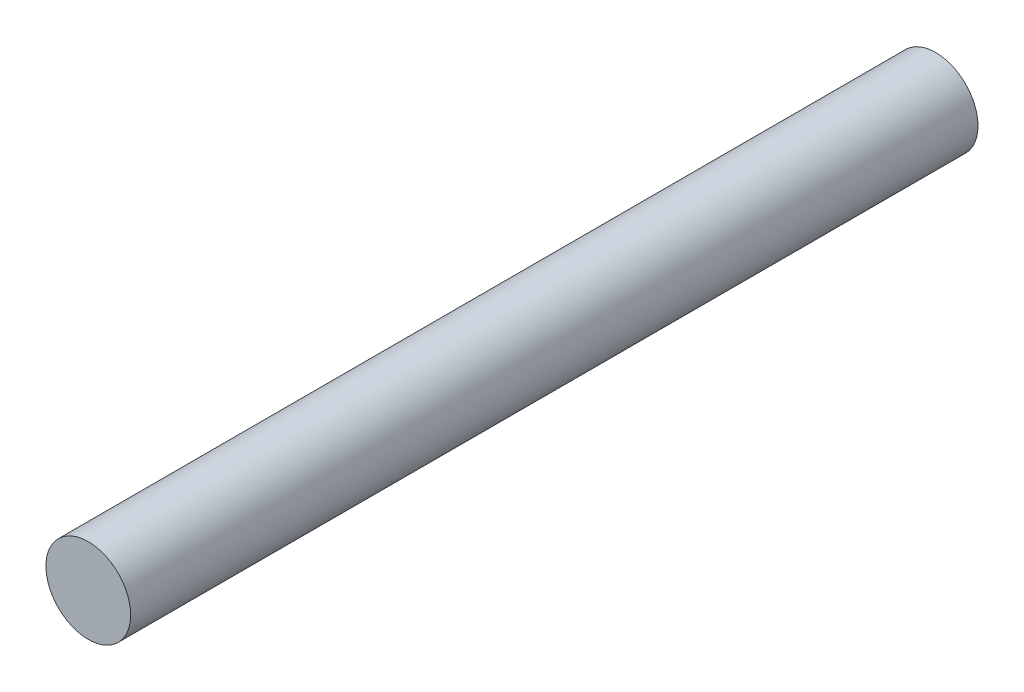
SolidWorks part; units mm, degrees
ref_plane "Front Plane" through (0, 0, 0) normal (0, 0, 1) x (1, 0, 0)
ref_plane "Top Plane" through (0, 0, 0) normal (0, 1, 0) x (1, 0, 0)
ref_plane "Right Plane" through (0, 0, 0) normal (1, 0, 0) x (0, 0, -1)
sketch "Sketch1" plane through (0, 0, 0) normal (0, 1, 0) x (1, 0, 0)
  line L0 (63.5, 0) -> (0, 0)
  line L1 (0, 0) -> (0, -1270)
  line L2 (0, -1270) -> (63.5, -1270)
  line L3 (63.5, -1270) -> (63.5, 0)
  line L4 (0, 0) -> (0, -1270) construction
revolve "Revolve1" add sketch "Sketch1" angle 360 about L4
